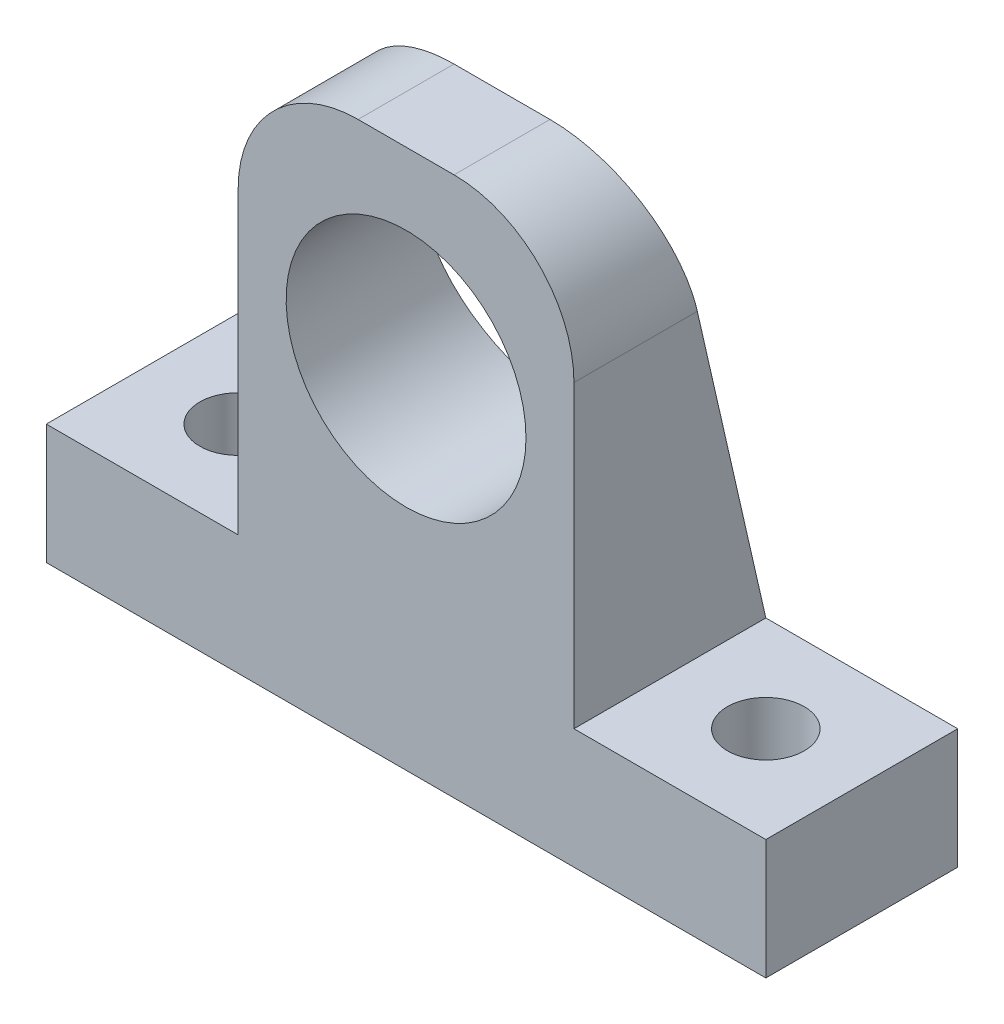
SolidWorks part; units mm, degrees
ref_plane "Front Plane" through (0, 0, 0) normal (0, 0, 1) x (1, 0, 0)
ref_plane "Top Plane" through (0, 0, 0) normal (0, 1, 0) x (1, 0, 0)
ref_plane "Right Plane" through (0, 0, 0) normal (1, 0, 0) x (0, 0, -1)
sketch "Sketch1" plane through (0, 0, 0) normal (0, 0, 1) x (1, 0, 0)
  line L0 (0, 0) -> (-15, 0)
  line L1 (0, 0) -> (15, 0)
  line L2 (0, 0) -> (0, 14.5) construction
  line L3 (-15, 0) -> (-15, 5)
  line L4 (15, 0) -> (15, 5)
  line L5 (-15, 5) -> (-7, 5)
  line L6 (15, 5) -> (7, 5)
  line L7 (7, 5) -> (7, 17.5)
  line L8 (-7, 5) -> (-7, 17.5)
  line L9 (-2, 22.5) -> (2, 22.5)
  circle A0 centre (0, 14.5) radius 5
  arc A1 (7, 17.5) -> (2, 22.5) centre (2, 17.5) ccw
  arc A2 (-7, 17.5) -> (-2, 22.5) centre (-2, 17.5) cw
  dimension "D1" = 5
extrude "Boss-Extrude1" add sketch "Sketch1" along normal blind 8
sketch "Sketch2" plane through (0, 5, 0) normal (0, 1, 0) x (1, 0, 0)
  line L0 (-15, -4) -> (-11, -4) construction
  line L1 (-15, -8) -> (-15, 0) construction
  line L2 (0, 0) -> (0, 4.4086) construction
  line L3 (2, 0) -> (-2, 0) construction
  circle A0 centre (-11, -4) radius 1.6
  circle A1 centre (11, -4) radius 1.6
extrude "Cut-Extrude1" cut sketch "Sketch2" against normal blind 10
sketch "Sketch3" plane through (-15, 0, 0) normal (-1, 0, 0) x (0, 0, 1)
  line L0 (0, 5) -> (4, 22.5)
  line L1 (8, 22.5) -> (0, 22.5) construction
extrude "Cut-Extrude2" cut sketch "Sketch3" against normal through all and the other way through all
